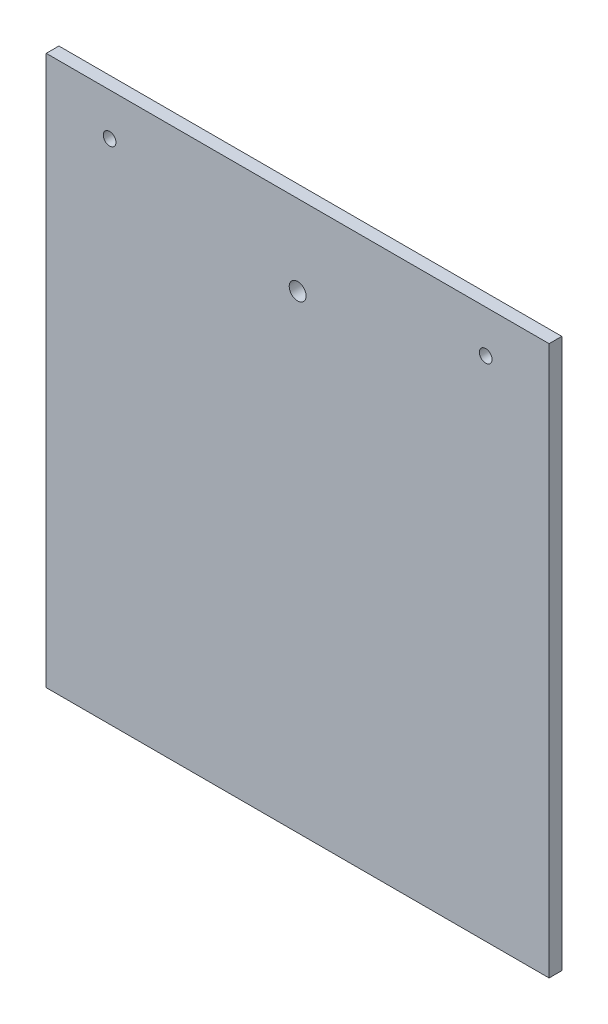
SolidWorks part; units mm, degrees
ref_plane "前视基准面" through (0, 0, 0) normal (0, 0, 1) x (1, 0, 0)
ref_plane "上视基准面" through (0, 0, 0) normal (0, 1, 0) x (1, 0, 0)
ref_plane "右视基准面" through (0, 0, 0) normal (1, 0, 0) x (0, 0, -1)
other "Configuration Table"
sketch "草图1" plane through (0, 0, 0) normal (0, 0, 1) x (1, 0, 0)
  line L1 (59.5, -65) -> (-59.5, -65)
  line L2 (59.5, -65) -> (59.5, 65)
  line L3 (59.5, 65) -> (-59.5, 65)
  line L4 (-59.5, -65) -> (-59.5, 65)
  line L5 (59.5, -65) -> (-59.5, 65) construction
  line L6 (59.5, 65) -> (-59.5, -65) construction
  point P0 (0, 0)
  dimension "D1" = 119
  dimension "D2" = 130
extrude "凸台-拉伸1" add sketch "草图1" along normal blind 3
sketch "草图2" plane through (0, 0, 3) normal (0, 0, 1) x (1, 0, 0)
  line L0 (59.5, 65) -> (-59.5, 65) construction
  line L1 (59.5, -65) -> (59.5, 65) construction
  line L2 (0, 65) -> (0, 44.368) construction
  circle A0 centre (44.5, 55) radius 1.5
  circle A1 centre (-44.5, 55) radius 1.5
  dimension "D1" = 10
  dimension "D3" = 3
  dimension "D2" = 15
extrude "切除-拉伸1" cut sketch "草图2" against normal through all contours A0 | A1
sketch "草图4" plane through (0, 0, 3) normal (0, 0, 1) x (1, 0, 0)
  line L0 (0, 65) -> (0, 42) construction
  line L1 (59.5, 65) -> (-59.5, 65) construction
  line L2 (0, 42) -> (0, 46) construction
  circle A0 centre (0, 46) radius 2
  dimension "D2" = 4
  dimension "D3" = 4
  dimension "D1" = 23
extrude "切除-拉伸2" cut sketch "草图4" against normal through all
